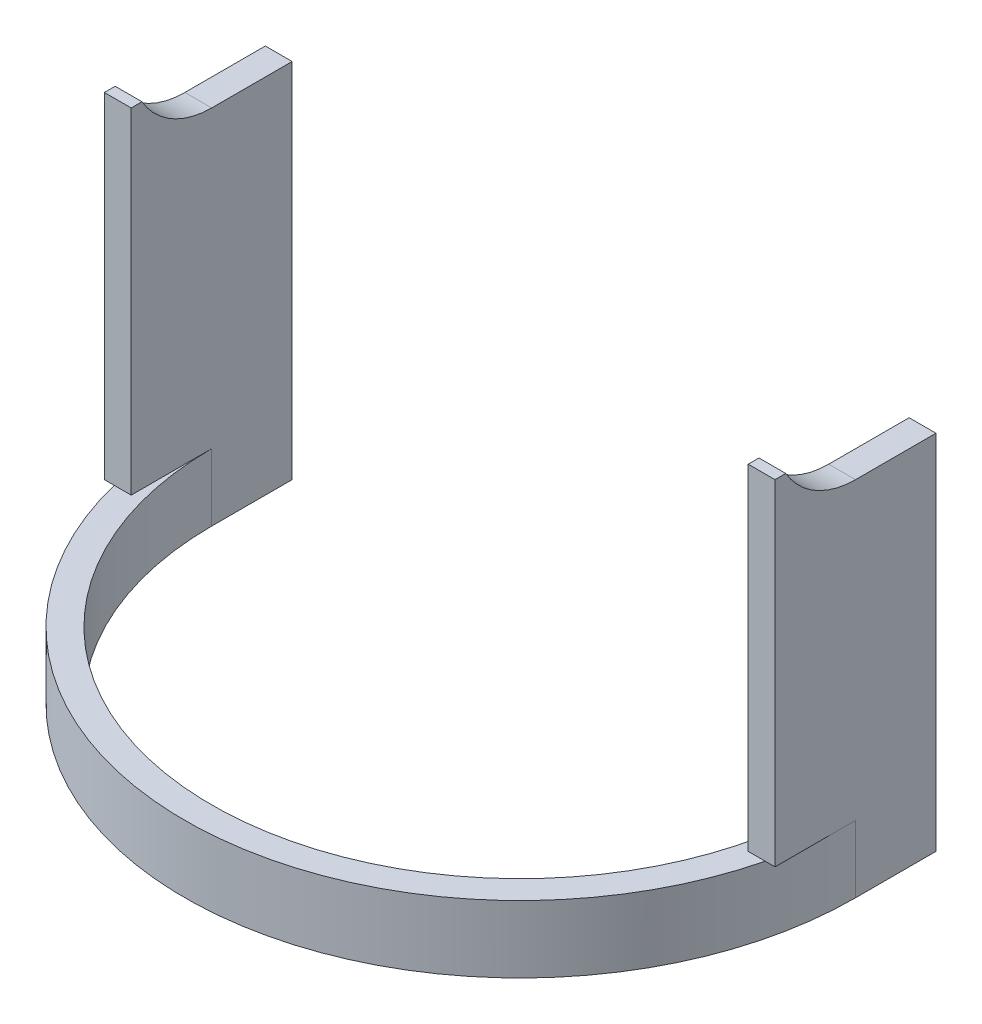
SolidWorks part; units mm, degrees
ref_plane "Front" through (0, 0, 0) normal (0, 0, 1) x (1, 0, 0)
ref_plane "Top" through (0, 0, 0) normal (0, 1, 0) x (1, 0, 0)
ref_plane "Right" through (0, 0, 0) normal (1, 0, 0) x (0, 0, -1)
sketch "草图1" plane through (0, 0, 0) normal (0, 1, 0) x (1, 0, 0)
  line L0 (-50, 0) -> (0, 0) construction
  line L1 (0, 0) -> (0, 52.3913) construction
  line L3 (-50, 12) -> (-46, 12)
  line L4 (-50, 12) -> (-50, 0)
  line L6 (-46, 12) -> (-46, 0)
  line L7 (50, 12) -> (46, 12)
  line L8 (50, 12) -> (50, 0)
  line L10 (46, 12) -> (46, 0)
  arc A0 (-50, 0) -> (50, 0) centre (0, 0) ccw
  arc A1 (-46, 0) -> (46, 0) centre (0, 0) ccw
  dimension "D3" = 50
  dimension "D7" = 4
  dimension "D8" = 50
extrude "凸台-拉伸1" add sketch "草图1" along normal blind 10
sketch "草图2" plane through (0, 10, 0) normal (0, 1, 0) x (1, 0, 0)
  line L0 (0, 0) -> (0, 19.9833) construction
  line L1 (-50, 12) -> (-46, 12)
  line L2 (-50, 12) -> (-50, -12)
  line L3 (-50, -12) -> (-46, -12)
  line L4 (-46, 12) -> (-46, -12)
  line L5 (50, 12) -> (46, 12)
  line L6 (50, 12) -> (50, -12)
  line L7 (50, -12) -> (46, -12)
  line L8 (46, 12) -> (46, -12)
  dimension "D1" = 24
  dimension "D2" = 24
  dimension "D3" = 4
  dimension "D4" = 4
extrude "凸台-拉伸2" add sketch "草图2" along normal blind 50
sketch "草图3" plane through (50, 0, 0) normal (1, 0, 0) x (0, 0, -1)
  line L0 (0, 60) -> (0, 38.5038) construction
  line L1 (-12, 60) -> (12, 60) construction
  line L8 (0, 54) -> (12, 54)
  line L9 (12, 60) -> (12, 0) construction
  line L10 (12, 54) -> (12, 66)
  arc A1 (12, 66) -> (0, 54) centre (0, 66) ccw
extrude "切除-拉伸3" cut sketch "草图3" against normal through all
